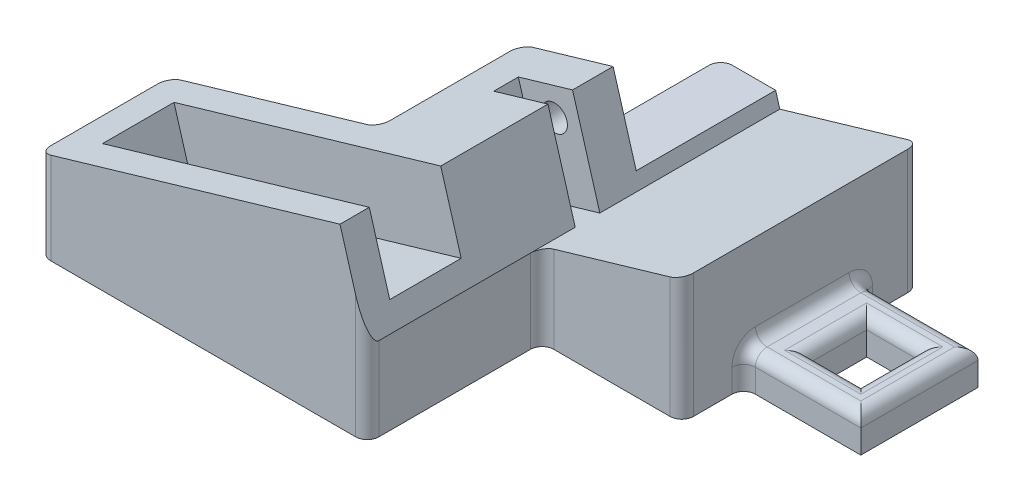
SolidWorks part; units mm, degrees
ref_plane "Front Plane" through (0, 0, 0) normal (0, 0, 1) x (1, 0, 0)
ref_plane "Top Plane" through (0, 0, 0) normal (0, 1, 0) x (1, 0, 0)
ref_plane "Right Plane" through (0, 0, 0) normal (1, 0, 0) x (0, 0, -1)
sketch "Sketch2" plane through (0, 0, 0) normal (0, 1, 0) x (1, 0, 0)
  line L1 (-15.1142, 12.6386) -> (28.8622, 12.6386)
  line L2 (-15.1142, 12.6386) -> (-15.1142, -24.7677)
  line L3 (-15.1142, -24.7677) -> (28.8622, -24.7677)
  line L4 (28.8622, 12.6386) -> (28.8622, -24.7677)
extrude "Boss-Extrude1" add sketch "Sketch2" along normal blind 3
sketch "Sketch3" plane through (0, 0, 0) normal (0, 0, 1) x (1, 0, 0)
  line L0 (3.3227, 11.74) -> (-2.8846, 9.9195)
  line L1 (-2.8846, 9.9195) -> (-11.0544, 7.5234)
  line L2 (-11.0544, 7.5234) -> (-11.0544, 3)
  line L3 (-11.0544, 3) -> (28.8622, 3)
  line L4 (-15.1142, 3) -> (28.8622, 3) construction
  line L5 (28.8622, 3) -> (28.8622, 10.6097)
  line L6 (28.8622, 10.6097) -> (16.9496, 7.1159)
  line L7 (16.9496, 7.1159) -> (14.6215, 15.0538)
  line L8 (14.6215, 15.0538) -> (3.3227, 11.74)
extrude "Boss-Extrude2" add sketch "Sketch3" along normal up to surface and the other way up to surface up to face at (6.874, 1.5, 24.7677) other way up to face at (6.874, 1.5, -12.6386)
sketch "Sketch4" plane through (-2.9073, 9.9128, 0) normal (-0.2814, 0.9596, 0) x (0.9596, 0.2814, 0)
  line L0 (18.2671, 12.6386) -> (18.2671, -24.7677) construction
  line L1 (18.2671, -13.972) -> (-5.4575, -13.972)
  line L2 (18.2671, -13.972) -> (18.2671, -20.072)
  line L3 (18.2671, -20.072) -> (-5.4575, -20.072)
  line L4 (-5.4575, -13.972) -> (-5.4575, -20.072)
extrude "Cut-Extrude1" cut sketch "Sketch4" against normal blind 6.2
sketch "Sketch5" plane through (-0.2956, 0, 0) normal (0, 1, 0) x (1, 0, 0)
  line L0 (17.2451, 12.6386) -> (17.2451, -24.7677) construction
  line L1 (30.6815, -24.7677) -> (17.2451, -24.7677)
  line L2 (30.6815, -24.7677) -> (30.6815, -7.6482)
  line L3 (30.6815, -7.6482) -> (17.2451, -7.6482)
  line L4 (17.2451, -24.7677) -> (17.2451, -7.6482)
extrude "Cut-Extrude2" cut sketch "Sketch5" along normal through all
sketch "Sketch6" plane through (0, 3, 0) normal (0, 1, 0) x (1, 0, 0)
  line L0 (-15.1142, -24.7677) -> (-11.0544, -24.7677) construction
  line L1 (-15.1142, -24.7677) -> (16.9496, -24.7677)
  line L2 (-15.1142, -24.7677) -> (-15.1142, -22.572)
  line L3 (-15.1142, -22.572) -> (16.9496, -22.572)
  line L4 (16.9496, -24.7677) -> (16.9496, -22.572)
  line L5 (16.9496, -7.6482) -> (16.9496, -24.7677) construction
  line L6 (-8.1442, -20.072) -> (14.6215, -20.072) construction
  dimension "D1" = 2.5
extrude "Cut-Extrude3" cut sketch "Sketch6" against normal through all and the other way through all
sketch "Sketch7" plane through (0, 3, 0) normal (0, 1, 0) x (1, 0, 0)
  line L0 (-11.0544, -22.572) -> (-11.0544, 12.6386) construction
  line L1 (-11.0544, 12.6386) -> (6.8051, 12.6386)
  line L2 (-11.0544, 12.6386) -> (-11.0544, -11.472)
  line L3 (-11.0544, -11.472) -> (6.8051, -11.472)
  line L4 (6.8051, 12.6386) -> (6.8051, -11.472)
  line L5 (14.6215, -13.972) -> (-8.1442, -13.972) construction
  dimension "D1" = 2.5
extrude "Cut-Extrude4" cut sketch "Sketch7" along normal through all
sketch "Sketch9" plane through (-2.9073, 9.9128, 0) normal (-0.2814, 0.9596, 0) x (0.9596, 0.2814, 0)
  line L0 (18.546, -2.7231) -> (13.446, -2.7231)
  line L1 (18.296, -2.9731) -> (13.696, -2.9731) construction
  line L2 (18.296, -2.9731) -> (18.296, -4.5731) construction
  line L3 (18.296, -4.5731) -> (13.696, -4.5731) construction
  line L4 (13.696, -2.9731) -> (13.696, -4.5731) construction
  line L5 (13.446, -2.7231) -> (13.446, -4.8231)
  line L6 (18.546, -4.8231) -> (13.446, -4.8231)
  line L7 (18.546, -2.7231) -> (18.546, -4.8231)
  dimension "D1" = 0.25
extrude "Cut-Extrude5" cut sketch "Sketch9" against normal up to surface (8.2722 mm away) up to face at (22.9059, 8.8628, -2.4952)
sketch "Sketch10" plane through (0, 3, 0) normal (0, 1, 0) x (1, 0, 0)
  line L0 (-11.0544, -22.572) -> (14.6215, -22.572) construction
  line L1 (-11.0544, -22.572) -> (-15.1142, -22.572)
  line L2 (-11.0544, -22.572) -> (-11.0544, 12.6386)
  line L3 (-11.0544, 12.6386) -> (-15.1142, 12.6386)
  line L4 (-15.1142, -22.572) -> (-15.1142, 12.6386)
  line L5 (-11.0544, -22.572) -> (-11.0544, -11.472) construction
  line L6 (-15.1142, 12.6386) -> (-15.1142, -22.572) construction
extrude "Cut-Extrude6" cut sketch "Sketch10" against normal through all
sketch "Sketch11" plane through (0, 0, -12.6386) normal (0, 0, -1) x (-1, 0, 0)
  line L0 (-6.8051, 3) -> (-11.9066, 3)
  line L1 (-6.8051, 3) -> (11.0544, 3) construction
  line L2 (-6.8051, 12.7613) -> (-6.8051, 3) construction
  line L3 (-11.9066, 3) -> (-11.9066, 14.2575)
  line L4 (-6.8051, 12.7613) -> (-14.6215, 15.0538) construction
  line L5 (-11.9066, 14.2575) -> (-6.8051, 12.7613)
  line L6 (-6.8051, 12.7613) -> (-6.8051, 3)
extrude "Cut-Extrude7" cut sketch "Sketch11" against normal blind 11.9
sketch "Sketch14" plane through (28.8622, 0, 0) normal (1, 0, 0) x (0, 0, -1)
  line L0 (-7.6482, 0) -> (12.6386, 0) construction
  line L1 (7.6386, 0) -> (-2.3614, 0)
  line L2 (7.6386, 0) -> (7.6386, 3)
  line L3 (7.6386, 3) -> (-2.3614, 3)
  line L4 (-2.3614, 0) -> (-2.3614, 3)
  line L5 (12.6386, 10.6097) -> (12.6386, 0) construction
  dimension "D1" = 10
  dimension "D2" = 3
  dimension "D3" = 5
extrude "Boss-Extrude3" add sketch "Sketch14" along normal blind 10
sketch "Sketch15" plane through (0, 3, 0) normal (0, 1, 0) x (1, 0, 0)
  line L0 (38.8622, 7.6386) -> (38.8622, -2.3614) construction
  line L1 (31.8622, 0.1386) -> (36.3622, 0.1386)
  line L2 (31.8622, 0.1386) -> (31.8622, 5.1386)
  line L3 (31.8622, 5.1386) -> (36.3622, 5.1386)
  line L4 (36.3622, 0.1386) -> (36.3622, 5.1386)
  line L5 (38.8622, -2.3614) -> (28.8622, -2.3614) construction
  line L6 (38.8622, 7.6386) -> (28.8622, 7.6386) construction
  line L7 (28.8622, 7.6386) -> (28.8622, -2.3614) construction
  dimension "D1" = 2.5
  dimension "D2" = 2.5
  dimension "D3" = 2.5
  dimension "D4" = 3
extrude "Cut-Extrude8" cut sketch "Sketch15" against normal through all
fillet "Fillet1" radius 1 10 edges at (33.8622, 3, -7.6386) (38.8622, 3, -2.6386) (33.8622, 3, 2.3614) (28.8622, 3, -2.6386) (36.3622, 3, -2.6386) (34.1122, 3, -5.1386) (31.8622, 3, -2.6386) (34.1122, 3, -0.1386)
sketch "Sketch17" plane through (-1.9145, 3, 0) normal (0, 1, 0) x (1, 0, 0)
  line L0 (13.8211, 12.6386) -> (13.8211, 0.7386)
  line L1 (13.8211, 0.7386) -> (13.8211, 12.6386) construction
  line L2 (8.7195, 0.7386) -> (13.8211, 0.7386) construction
  line L3 (13.8211, 0.7386) -> (8.7195, 0.7386)
  line L4 (8.7195, 0.7386) -> (8.7195, -11.472)
  line L5 (8.7195, -11.472) -> (8.7195, 0.7386) construction
  line L6 (8.7195, -11.472) -> (-9.1399, -11.472)
  line L7 (-9.1399, -22.572) -> (-9.1399, -11.472) construction
  line L8 (-9.1399, -11.472) -> (8.7195, -11.472) construction
  line L9 (-9.1399, -11.472) -> (-9.1399, 12.6386)
  line L10 (-9.1399, 12.6386) -> (13.8211, 12.6386)
extrude "Cut-Extrude9" cut sketch "Sketch17" against normal through all
sketch "Sketch18" plane through (0, 0, -12.6386) normal (0, 0, -1) x (-1, 0, 0)
  line L0 (-16.9496, 7.1159) -> (-11.9066, 5.6369)
  line L1 (-11.9066, 14.2575) -> (-11.9066, 0) construction
  line L2 (-11.9066, 5.6369) -> (-11.9066, 14.2575)
  line L3 (-11.9066, 14.2575) -> (-14.6215, 15.0538)
  line L4 (-14.6215, 15.0538) -> (-16.9496, 7.1159)
extrude "Cut-Extrude10" cut sketch "Sketch18" against normal up to surface (11.9 mm away) up to face at (9.3558, 6.7547, -0.7386)
sketch "Sketch19" plane through (0, 0, 2.7231) normal (0, 0, 1) x (1, 0, 0)
  circle A0 centre (13.084, 12.2261) radius 1.1
extrude "Cut-Extrude11" cut sketch "Sketch19" against normal through all
sketch "Sketch21" plane through (0, 0, -0.7386) normal (0, 0, -1) x (-1, 0, 0)
  line L0 (-16.9496, 7.1159) -> (-11.9066, 5.6369)
  line L1 (-16.9496, 7.1159) -> (-11.9066, 5.6369) construction
  line L2 (-14.6215, 15.0538) -> (-16.9496, 7.1159) construction
  line L3 (-11.9066, 5.6369) -> (-11.9066, 8.3319)
  line L4 (-11.9066, 8.3319) -> (-16.5929, 8.3319)
  line L5 (-16.5929, 8.3319) -> (-16.9496, 7.1159)
extrude "Boss-Extrude4" add sketch "Sketch21" along normal up to surface (11.9 mm away) up to face at (20.3844, 4.0616, -12.6386)
fillet "Fillet2" radius 1 10 edges at (16.9496, 3.558, 7.6482) (16.9496, 3.558, 22.572) (28.8622, 5.3049, 7.6482) (28.8622, 5.3049, -12.6386) (11.9066, 4.166, -0.7386) (11.9066, 4.166, -12.6386) (-11.0544, 3.7617, 11.472) (-11.0544, 3.7617, 22.572) (6.8051, 6.3807, -0.7386) (6.8051, 6.3807, 11.472)
sketch "Sketch22" plane through (0, 0, 11.472) normal (0, 0, -1) x (-1, 0, 0)
  line L0 (10.0544, 0) -> (-5.8051, 0) construction
  line L1 (-6.8051, 0) -> (3.1949, 0)
  line L2 (-6.8051, 0) -> (-6.8051, 3)
  line L3 (-6.8051, 3) -> (3.1949, 3)
  line L4 (3.1949, 0) -> (3.1949, 3)
  line L6 (-6.8051, 0) -> (-6.8051, 12.7613) construction
  dimension "D1" = 10
  dimension "D2" = 0
extrude "Boss-Extrude5" add sketch "Sketch22" along normal blind 10
sketch "Sketch23" plane through (0, 3, 0) normal (0, 1, 0) x (1, 0, 0)
  line L0 (-3.1949, -1.472) -> (6.8051, -1.472) construction
  line L1 (5.3845, -8.972) -> (-0.6949, -8.972)
  line L2 (5.3845, -8.972) -> (5.3845, -3.972)
  line L3 (5.3845, -3.972) -> (-0.6949, -3.972)
  line L4 (-0.6949, -8.972) -> (-0.6949, -3.972)
  line L5 (-3.1949, -1.472) -> (-3.1949, -11.472) construction
  line L6 (-3.1949, -11.472) -> (5.8051, -11.472) construction
  dimension "D1" = 2.5
  dimension "D2" = 2.5
  dimension "D3" = 2.5
extrude "Cut-Extrude12" cut sketch "Sketch23" against normal through all
fillet "Fillet4" radius 1 7 edges at (-3.1949, 1.5, 1.472) (1.8051, 3, 1.472) (-3.1949, 3, 6.472) (-0.6949, 3, 6.472) (2.3448, 3, 3.972) (5.3845, 3, 6.472) (2.3448, 3, 8.972)
